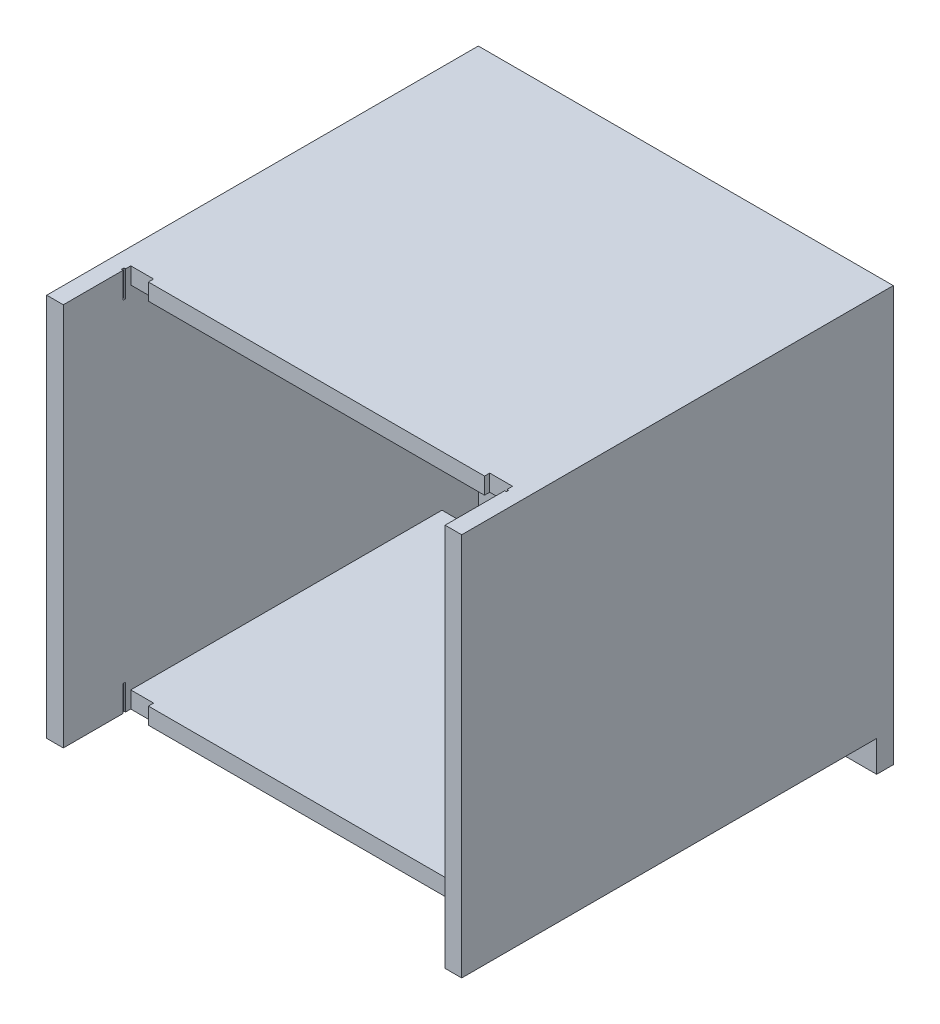
SolidWorks part; units mm, degrees
ref_plane "前视基准面" through (0, 0, 0) normal (0, 0, 1) x (1, 0, 0)
ref_plane "上视基准面" through (0, 0, 0) normal (0, 1, 0) x (1, 0, 0)
ref_plane "右视基准面" through (0, 0, 0) normal (1, 0, 0) x (0, 0, -1)
sketch "草图1" plane through (0, 0, 0) normal (0, 0, 1) x (1, 0, 0)
  line L0 (386.4133, -13.4264) -> (-13.5867, -13.4264)
  line L1 (-13.5867, -13.4264) -> (-13.5867, 386.5736)
  line L2 (-13.5867, 386.5736) -> (386.4133, 386.5736)
  line L3 (386.4133, 386.5736) -> (386.4133, -13.4264)
extrude "凸台-拉伸1" add sketch "草图1" along normal blind 16
sketch "草图2" plane through (0, 0, 16) normal (0, 0, 1) x (1, 0, 0)
  line L0 (-13.5867, 386.5736) -> (2.4133, 386.5736)
  line L1 (386.4133, 386.5736) -> (-13.5867, 386.5736) construction
  line L2 (2.4133, 386.5736) -> (2.4133, 16.5736)
  line L4 (2.4133, 16.5736) -> (-13.5867, 16.5736)
  line L5 (-13.5867, 16.5736) -> (-13.5867, 386.5736)
extrude "凸台-拉伸2" add sketch "草图2" along normal blind 400
sketch "草图3" plane through (0, 0, 16) normal (0, 0, 1) x (1, 0, 0)
  line L0 (386.4133, 386.5736) -> (370.4133, 386.5736)
  line L1 (386.4133, 386.5736) -> (2.4133, 386.5736) construction
  line L2 (370.4133, 386.5736) -> (370.4133, 16.5736)
  line L3 (370.4133, 16.5736) -> (386.4133, 16.5736)
  line L4 (386.4133, -13.4264) -> (386.4133, 386.5736) construction
  line L5 (386.4133, 16.5736) -> (386.4133, 386.5736)
  point P5 (0, 0)
  point P11 (0, 0)
  point P12 (0, 0)
  point P13 (0, 0)
  point P14 (0, 0)
  point P15 (0, 0)
  point P16 (0, 0)
  point P17 (0, 0)
  point P18 (0, 0)
extrude "凸台-拉伸3" add sketch "草图3" along normal blind 400
sketch "草图4" plane through (0, 0, 16) normal (0, 0, 1) x (1, 0, 0)
  line L0 (2.4133, 386.5736) -> (2.4133, 370.5736)
  line L1 (2.4133, 16.5736) -> (2.4133, 386.5736) construction
  line L2 (2.4133, 370.5736) -> (370.4133, 370.5736)
  line L3 (370.4133, 386.5736) -> (370.4133, 16.5736) construction
  line L4 (370.4133, 370.5736) -> (370.4133, 386.5736)
  line L5 (386.4133, 386.5736) -> (370.4133, 386.5736) construction
  line L6 (370.4133, 386.5736) -> (370.4133, 16.5736) construction
  line L7 (370.4133, 386.5736) -> (2.4133, 386.5736)
extrude "凸台-拉伸4" add sketch "草图4" along normal blind 340
sketch "草图6" plane through (370.4133, 0, 0) normal (-1, 0, 0) x (0, 0, 1)
  line L0 (356, 16.5736) -> (356, 32.5736)
  line L1 (416, 16.5736) -> (16, 16.5736) construction
  line L2 (356, 32.5736) -> (51, 32.5736)
  line L3 (51, 32.5736) -> (51, 16.5736)
  line L4 (51, 16.5736) -> (356, 16.5736)
  line L5 (16, 370.5736) -> (16, 16.5736) construction
  dimension "D1" = 16
  dimension "D2" = 305
  dimension "D3" = 35
extrude "凸台-拉伸5" add sketch "草图6" along normal up to next
sketch "草图7" plane through (0, 0, 356) normal (0, 0, 1) x (1, 0, 0)
  line L0 (348.4133, 16.5736) -> (348.4133, 32.5736)
  line L1 (2.4133, 16.5736) -> (370.4133, 16.5736) construction
  line L2 (2.4133, 32.5736) -> (370.4133, 32.5736) construction
  line L3 (348.4133, 32.5736) -> (370.4133, 32.5736)
  line L4 (370.4133, 32.5736) -> (370.4133, 16.5736)
  line L5 (370.4133, 16.5736) -> (348.4133, 16.5736)
  dimension "D1" = 22
extrude "切除-拉伸1" cut sketch "草图7" against normal blind 5
sketch "草图14" plane through (0, 0, 356) normal (0, 0, 1) x (1, 0, 0)
  line L0 (24.4133, 32.5736) -> (24.4133, 16.5736)
  line L1 (2.4133, 32.5736) -> (348.4133, 32.5736) construction
  line L2 (2.4133, 16.5736) -> (348.4133, 16.5736) construction
  line L3 (24.4133, 16.5736) -> (2.4133, 16.5736)
  line L4 (2.4133, 16.5736) -> (2.4133, 32.5736)
  line L5 (2.4133, 16.5736) -> (2.4133, 32.5736) construction
  line L6 (2.4133, 32.5736) -> (24.4133, 32.5736)
  dimension "D1" = 22
extrude "切除-拉伸2" cut sketch "草图14" against normal blind 5
ref_plane "基准面5" through (0, 201.5736, 0) normal (0, -1, 0) x (-1, 0, 0)
mirror "镜向1" about plane through (0, 201.5736, 0) normal (0, -1, 0) of "切除-拉伸2", "切除-拉伸1"
sketch "草图15" plane through (0, 16.5736, 0) normal (0, -1, 0) x (1, 0, 0)
  line L0 (2.4133, 356) -> (0.9133, 356)
  line L1 (2.4133, 416) -> (2.4133, 351) construction
  line L2 (0.9133, 356) -> (0.9133, 358.5)
  line L3 (0.9133, 358.5) -> (2.4133, 358.5)
  line L4 (2.4133, 358.5) -> (2.4133, 356)
  point P4 (0, 0)
  point P7 (0, 0)
  point P8 (0, 0)
  dimension "D1" = 1.5
  dimension "D2" = 2.5
extrude "切除-拉伸3" cut sketch "草图15" against normal blind 25 contours L2 L3 L4 L0
mirror "镜向2" about plane through (0, 201.5736, 0) normal (0, -1, 0) of "切除-拉伸3"
ref_plane "基准面6" through (186.4133, 0, 0) normal (1, 0, 0) x (0, 0, -1)
mirror "镜向3" about plane through (186.4133, 0, 0) normal (1, 0, 0) of "切除-拉伸3"
mirror "镜向4" about plane through (0, 201.5736, 0) normal (0, -1, 0) of "镜向2", "镜向3"
